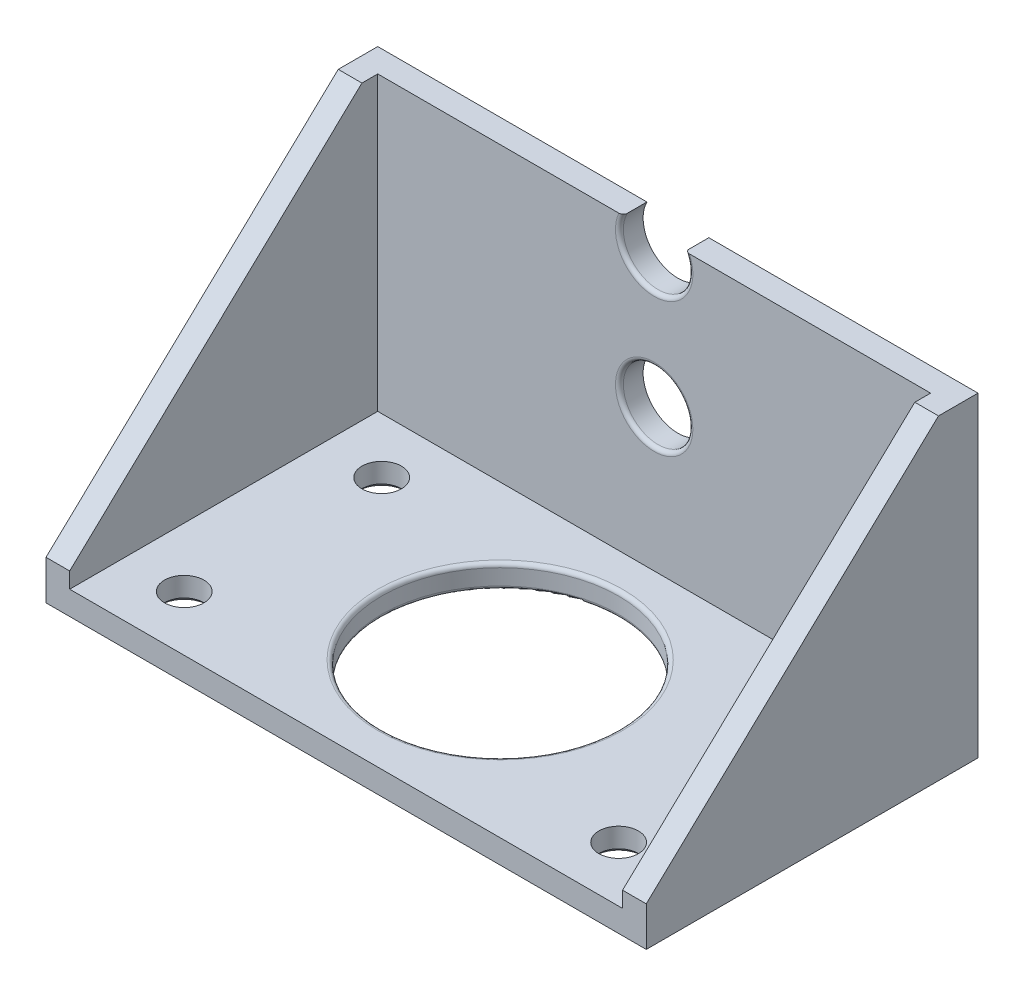
SolidWorks part; units mm, degrees
ref_plane "前视基准面" through (0, 0, 0) normal (0, 0, 1) x (1, 0, 0)
ref_plane "上视基准面" through (0, 0, 0) normal (0, 1, 0) x (1, 0, 0)
ref_plane "右视基准面" through (0, 0, 0) normal (1, 0, 0) x (0, 0, -1)
other "Configuration Table"
sketch "草图1" plane through (0, 0, 0) normal (0, 0, 1) x (1, 0, 0)
  line L0 (0, 0) -> (76, 0)
  line L1 (76, 0) -> (76, 40)
  line L2 (48, 70) -> (28, 70)
  line L3 (0, 40) -> (0, 0)
  line L4 (48, 70) -> (76, 40)
  line L5 (28, 70) -> (48, 70)
  line L7 (28, 70) -> (0, 40)
  dimension "D1" = 20
  dimension "D2" = 76
  dimension "D3" = 28
  dimension "D4" = 30
  dimension "D5" = 40
extrude "凸台-拉伸1" add sketch "草图1" along normal blind 3 contours L2 L7 L3 L0 L1 L4
sketch "草图2" plane through (0, 0, 3) normal (0, 0, 1) x (1, 0, 0)
  line L0 (76, 0) -> (76, 3)
  line L1 (76, 0) -> (76, 40) construction
  line L2 (76, 3) -> (0, 3)
  line L3 (0, 40) -> (0, 0) construction
  line L4 (0, 3) -> (0, 0)
  line L5 (0, 0) -> (76, 0)
extrude "凸台-拉伸2" add sketch "草图2" along normal blind 39
sketch "草图3" plane through (0, 3, 0) normal (0, 1, 0) x (1, 0, 0)
  line L0 (38, -42) -> (2, -42)
  line L1 (76, -42) -> (0, -42) construction
  line L2 (2, -42) -> (2, -3)
  line L3 (28, -3) -> (0, -3) construction
  line L4 (2, -3) -> (74, -3)
  line L5 (48, -3) -> (76, -3) construction
  line L6 (74, -3) -> (74, -42)
  line L7 (74, -42) -> (38, -42)
  line L8 (38, -42) -> (38, -3)
  line L10 (10.5, -10) -> (65.5, -10)
  line L11 (10.5, -10) -> (10.5, -35)
  line L12 (10.5, -35) -> (65.5, -35)
  line L13 (65.5, -10) -> (65.5, -35)
  line L14 (10.5, -10) -> (65.5, -35) construction
  line L15 (10.5, -35) -> (65.5, -10) construction
  circle A0 centre (65.5, -10) radius 3
  circle A1 centre (65.5, -35) radius 3
  circle A2 centre (10.5, -10) radius 3
  circle A3 centre (10.5, -35) radius 3
  point P10 (38, -22.5)
  dimension "D1" = 55
  dimension "D2" = 25
sketch "草图7" plane through (0, 0, 3) normal (0, 0, 1) x (1, 0, 0)
  line L0 (38, 70) -> (38, 3)
  line L1 (48, 70) -> (28, 70) construction
  line L2 (76, 3) -> (0, 3) construction
  circle A0 centre (38, 55) radius 4.4
  circle A1 centre (38, 38) radius 4.4
  circle A2 centre (38, 21) radius 4.4
  dimension "D1" = 15
  dimension "D2" = 17
  dimension "D3" = 17
  dimension "D4" = 8.8
  dimension "D5" = 8.8
  dimension "D6" = 8.8
extrude "切除-拉伸1" cut sketch "草图7" against normal blind 52 contours L0 A0 | L0 A0 | L0 A1 | L0 A1 | L0 A2 | L0 A2
sketch "草图8" plane through (0, 3, 0) normal (0, 1, 0) x (1, 0, 0)
  line L0 (76, -22.5) -> (0, -22.5)
  line L1 (76, -42) -> (76, -3) construction
  line L2 (0, -42) -> (0, -3) construction
  circle A0 centre (38, -22.5) radius 15
  dimension "D1" = 30
extrude "切除-拉伸2" cut sketch "草图8" against normal blind 52 contours L0 A0 | L0 A0
sketch "草图10" plane through (0, 0, 0) normal (-1, 0, 0) x (0, 0, 1)
  line L0 (3, 40) -> (5, 40)
  line L1 (42, 3) -> (42, 5)
  line L2 (42, 5) -> (5, 40)
  line L3 (3, 40) -> (3, 3)
  line L4 (3, 3) -> (42, 3)
extrude "凸台-拉伸3" add sketch "草图10" against normal blind 3
ref_plane "基准面1" through (38, 0, 0) normal (1, 0, 0) x (0, 0, -1)
mirror "镜向1" about plane through (38, 0, 0) normal (1, 0, 0) of "凸台-拉伸3"
hole_wizard "M6 螺纹孔2" positions "草图13" profile "草图14" tap size "M6" standard "GB" end condition through all
sketch "草图13" plane through (0, 0, 0) normal (0, -1, 0) x (-1, 0, 0)
  point P0 (-65.5, -10)
  point P3 (-10.5, -10)
  point P6 (-10.5, -35)
  point P9 (-65.5, -35)
sketch "草图14" plane through (65.5, 0, 10) normal (1, 0, 0) x (0, 0, -1)
  line L0 (0, 0) -> (0, 70)
  line L1 (0, 70) -> (2.5, 70)
  line L2 (2.5, 70) -> (2.5, 0.525)
  line L3 (2.5, 0.525) -> (3.025, 0)
  line L5 (3.025, 0) -> (0, 0)
  line L6 (-2.5, 0.525) -> (-3.025, 0) construction
  line L11 (0, -6.35) -> (0, 107.95) construction
  dimension "通孔螺纹孔钻头直径" = 5
  dimension "通孔螺纹孔钻头深度" = 70
  dimension "近端锥形沉头孔直径" = 6.05
  dimension "近端锥形沉头孔角度" = 90
cosmetic thread "孔螺蚊线5" parameters "D2"=6
cosmetic thread "孔螺蚊线6" parameters "D2"=6
cosmetic thread "孔螺蚊线7" parameters "D2"=6
cosmetic thread "孔螺蚊线8" parameters "D2"=6
fillet "圆角4" radius 5 2 edges at (48, 70, 1.5) (28, 70, 1.5)
fillet "圆角5" radius 0.5 5 edges at (38, 0, 37.5) (23, 3, 22.5) (42.4, 55, 3) (42.4, 21, 3) (42.4, 38, 3)
sketch "草图15" plane through (0, 0, 3) normal (0, 0, 1) x (1, 0, 0)
  line L0 (76, 5) -> (76, 40) construction
  line L1 (0, 40) -> (76, 40)
  line L2 (0, 40) -> (0, 71.4553)
  line L3 (0, 71.4553) -> (76, 71.4553)
  line L4 (76, 40) -> (76, 71.4553)
extrude "切除-拉伸3" cut sketch "草图15" against normal blind 21
